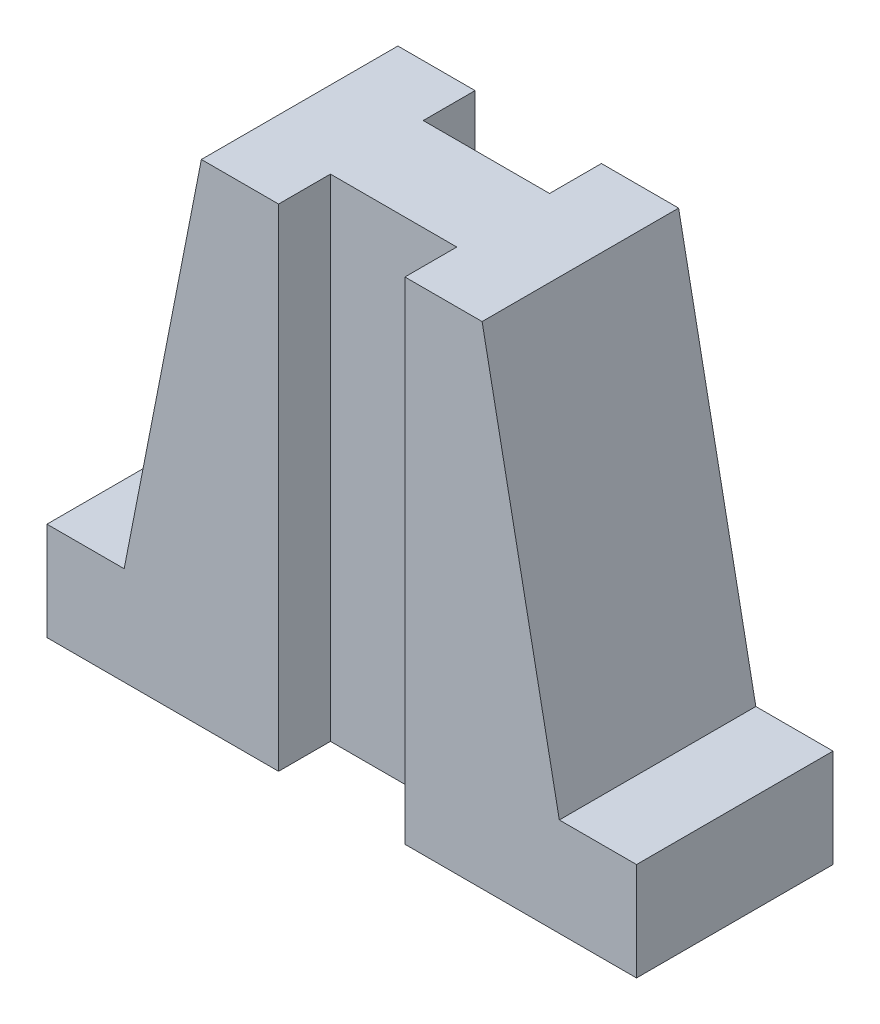
SolidWorks part; units mm, degrees
ref_plane "Alzado" through (0, 0, 0) normal (0, 0, 1) x (1, 0, 0)
ref_plane "Planta" through (0, 0, 0) normal (0, 1, 0) x (1, 0, 0)
ref_plane "Vista lateral" through (0, 0, 0) normal (1, 0, 0) x (0, 0, -1)
sketch "Croquis1" plane through (0, 0, 0) normal (0, 0, 1) x (1, 0, 0)
  line L0 (0, 0) -> (0, 70) construction
  line L1 (42, 0) -> (-42, 0)
  line L2 (-42, 0) -> (-42, 14)
  line L3 (-42, 14) -> (-31, 14)
  line L4 (-31, 14) -> (-20, 70)
  line L5 (-20, 70) -> (20, 70)
  line L6 (42, 0) -> (42, 14)
  line L7 (42, 14) -> (31, 14)
  line L8 (31, 14) -> (20, 70)
  dimension "D1" = 70
  dimension "D2" = 40
  dimension "D3" = 84
  dimension "D4" = 62
  dimension "D5" = 14
extrude "Saliente-Extruir1" add sketch "Croquis1" along normal mid plane 28
sketch "Croquis3" plane through (0, 70, 0) normal (0, 1, 0) x (1, 0, 0)
  line L0 (20, 14) -> (-20, 14) construction
  line L1 (-9, 14) -> (9, 14)
  line L2 (-9, 14) -> (-9, 6.6089)
  line L3 (-9, 6.6089) -> (9, 6.6089)
  line L4 (9, 14) -> (9, 6.6089)
  line L5 (0, 0) -> (17.9871, 0) construction
  line L6 (-9, -6.6089) -> (9, -6.6089)
  line L7 (-9, -14) -> (-9, -6.6089)
  line L8 (-9, -14) -> (9, -14)
  line L9 (9, -14) -> (9, -6.6089)
  point P13 (0, 6.6089)
  dimension "D1" = 18
  dimension "D2" = 13.2178
extrude "Cortar-Extruir1" cut sketch "Croquis3" against normal through all
